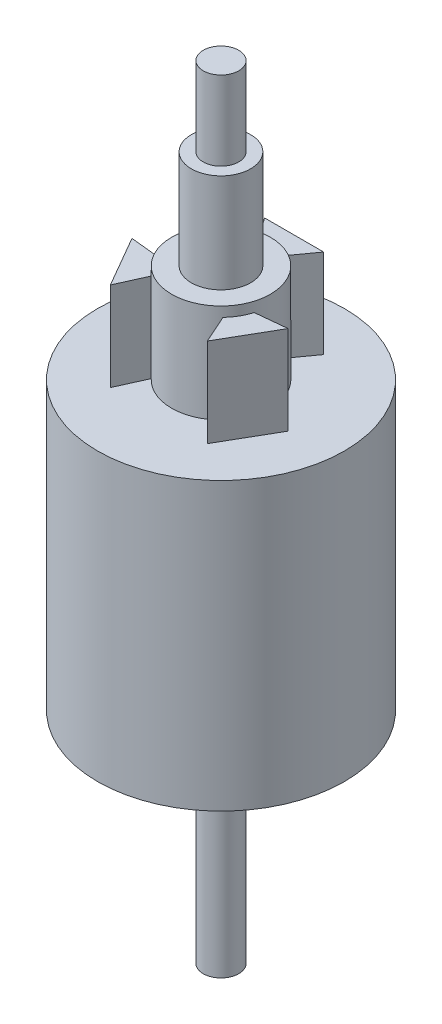
SolidWorks part; units mm, degrees
ref_plane "Front Plane" through (0, 0, 0) normal (0, 0, 1) x (1, 0, 0)
ref_plane "Top Plane" through (0, 0, 0) normal (0, 1, 0) x (1, 0, 0)
ref_plane "Right Plane" through (0, 0, 0) normal (1, 0, 0) x (0, 0, -1)
sketch "Sketch1" plane through (0, 0, 0) normal (0, 1, 0) x (1, 0, 0)
  circle A0 centre (0, 0) radius 6.25
  dimension "D1" = 12.5
extrude "Boss-Extrude1" add sketch "Sketch1" along normal blind 14.5
sketch "Sketch2" plane through (0, 0, 0) normal (0, 1, 0) x (1, 0, 0)
  circle A0 centre (0, 0) radius 0.9
  dimension "D1" = 1.8
extrude "Boss-Extrude2" add sketch "Sketch2" against normal blind 11.1
sketch "Sketch3" plane through (0, 14.5, 0) normal (0, 1, 0) x (1, 0, 0)
  circle A0 centre (0, 0) radius 2.5
  dimension "D1" = 5
extrude "Boss-Extrude3" add sketch "Sketch3" along normal blind 5
sketch "Sketch4" plane through (0, 19.5, 0) normal (0, 1, 0) x (1, 0, 0)
  circle A0 centre (0, 0) radius 1.5
  dimension "D1" = 3
extrude "Boss-Extrude4" add sketch "Sketch4" along normal blind 5
sketch "Sketch5" plane through (0, 24.5, 0) normal (0, 1, 0) x (1, 0, 0)
  circle A0 centre (0, 0) radius 0.9
  dimension "D1" = 1.8
extrude "Boss-Extrude5" add sketch "Sketch5" along normal blind 4
sketch "Sketch7" plane through (0, 14.5, 0) normal (0, 1, 0) x (1, 0, 0)
  line L2 (-0.5795, 2.4319) -> (-1.4953, 3.7007)
  line L4 (-1.4953, 3.7007) -> (1.4953, 3.7007)
  line L5 (0, 4.2459) -> (0, 0) construction
  line L6 (0.5795, 2.4319) -> (1.4953, 3.7007)
  circle A2 centre (0, 0) radius 2.5 construction
  arc A3 (0.5795, 2.4319) -> (-0.5795, 2.4319) centre (0, 0) ccw
  point P8 (0, 3.7007)
extrude "Boss-Extrude9" add sketch "Sketch7" along normal blind 4.5
pattern_circular "CirPattern1" count 3 every 120 about axis through (0, 0, 0) along (0, 1, 0) of "Boss-Extrude9"
